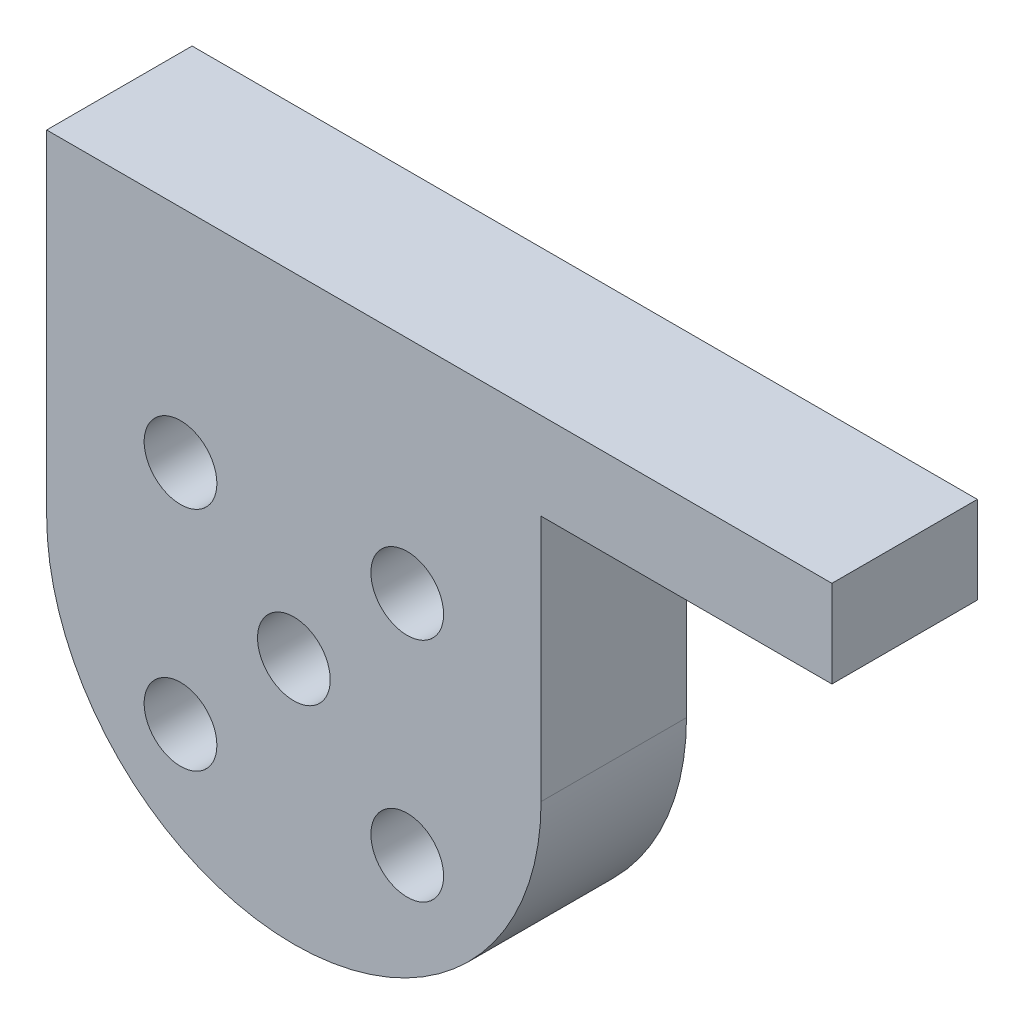
SolidWorks part; units mm, degrees
ref_plane "Front Plane" through (0, 0, 0) normal (0, 0, 1) x (1, 0, 0)
ref_plane "Top Plane" through (0, 0, 0) normal (0, 1, 0) x (1, 0, 0)
ref_plane "Right Plane" through (0, 0, 0) normal (1, 0, 0) x (0, 0, -1)
sketch "Sketch1" plane through (0, 0, 0) normal (0, 0, 1) x (1, 0, 0)
  line L0 (10.795, 0) -> (10.795, 10.795)
  line L1 (-4.95, 4.95) -> (4.95, 4.95) construction
  line L2 (-4.95, 4.95) -> (-4.95, -4.95) construction
  line L3 (-4.95, -4.95) -> (4.95, -4.95) construction
  line L4 (4.95, 4.95) -> (4.95, -4.95) construction
  line L5 (-4.95, 4.95) -> (4.95, -4.95) construction
  line L6 (-4.95, -4.95) -> (4.95, 4.95) construction
  line L7 (10.795, 10.795) -> (23.495, 10.795)
  line L8 (23.495, 10.795) -> (23.495, 14.605)
  line L9 (23.495, 14.605) -> (-10.795, 14.605)
  line L10 (-10.795, 14.605) -> (-10.795, 0)
  circle A0 centre (0, 0) radius 1.5875
  circle A1 centre (-4.95, 4.95) radius 1.5875
  circle A2 centre (-4.95, -4.95) radius 1.5875
  circle A3 centre (4.95, -4.95) radius 1.5875
  circle A4 centre (4.95, 4.95) radius 1.5875
  arc A5 (-10.795, 0) -> (10.795, 0) centre (0, 0) ccw
  arc A6 (10.795, 0) -> (-10.795, 0) centre (0, 0) ccw construction
  point P0 (0, 0)
  point P15 (-10.8929, 0)
  point P19 (0, 0)
  point P21 (13.1353, 10.795)
  dimension "D3" = 3.175
  dimension "D4" = 21.59
  dimension "D1" = 9.9
  dimension "D2" = 9.9
  dimension "D5" = 12.7
  dimension "D6" = 3.81
extrude "Boss-Extrude1" add sketch "Sketch1" along normal blind 6.35
